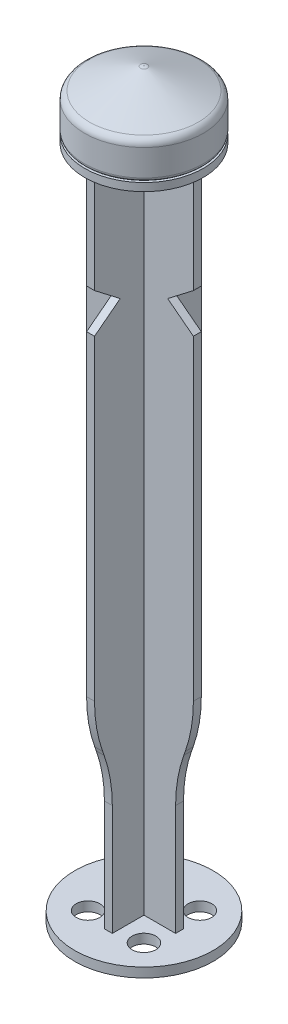
SolidWorks part; units mm, degrees
ref_plane "Front Plane" through (0, 0, 0) normal (0, 0, 1) x (1, 0, 0)
ref_plane "Top Plane" through (0, 0, 0) normal (0, 1, 0) x (1, 0, 0)
ref_plane "Right Plane" through (0, 0, 0) normal (1, 0, 0) x (0, 0, -1)
sketch "Sketch1" plane through (0, 0, 0) normal (0, 1, 0) x (1, 0, 0)
  circle A0 centre (0, 0) radius 8.75
  dimension "D1" = 17.5
extrude "Boss-Extrude1" add sketch "Sketch1" along normal blind 1.2
sketch "Sketch2" plane through (0, 1.2, 0) normal (0, 1, 0) x (1, 0, 0)
  line L1 (-0.5, 4.5) -> (0.5, 4.5)
  line L2 (-0.5, 4.5) -> (-0.5, 0)
  line L3 (-0.5, 0) -> (0.5, 0)
  line L4 (0.5, 4.5) -> (0.5, 0)
  point P9 (0, 0)
  dimension "D1" = 4.5
  dimension "D2" = 1
sketch "Sketch3" plane through (0, 0, 0) normal (1, 0, 0) x (0, 0, -1)
  line L0 (0, 1.2) -> (0, 85.2)
  line L1 (5.5318, 21.2068) -> (5.7182, 21.7331)
  line L4 (8.75, 1.2) -> (-8.75, 1.2) construction
  line L5 (4.5, 1.2) -> (4.5, 15.2)
  line L7 (6.75, 27.7399) -> (6.75, 67.7)
  line L8 (6.75, 67.7) -> (3.5, 70.2)
  line L9 (3.5, 70.2) -> (6.75, 72.7)
  line L10 (6.75, 72.7) -> (6.75, 85.2)
  line L11 (6.75, 85.2) -> (0, 85.2)
  line L12 (4.5, 1.2) -> (0, 1.2)
  arc A2 (6.75, 27.7399) -> (5.7182, 21.7331) centre (-11.25, 27.7399) cw
  arc A3 (4.5, 15.2) -> (5.5318, 21.2068) centre (22.5, 15.2) cw
  dimension "D9" = 14
  dimension "D8" = 18
  dimension "D1" = 84
  dimension "D2" = 4.5
  dimension "D3" = 6.75
  dimension "D4" = 6.75
  dimension "D5" = 3.5
  dimension "D6" = 15
  dimension "D7" = 5
  dimension "D10" = 26.5399
extrude "Boss-Extrude2" add sketch "Sketch3" against normal up to vertex (0.5 mm away) and the other way up to vertex (0.5 mm away) up to point (-0.5, 1.2, 0) other way up to point (0.5, 1.2, 0)
pattern_circular "CirPattern1" count 4 over 360 about axis through (0, 0, 0) along (0, 1, 0) of "Boss-Extrude2"
sketch "Sketch4" plane through (0, 85.2, 0) normal (0, 1, 0) x (1, 0, 0)
  circle A0 centre (0, 0) radius 7.5
  dimension "D1" = 15
extrude "Boss-Extrude3" add sketch "Sketch4" along normal blind 1
sketch "Sketch5" plane through (0, 0, 0) normal (1, 0, 0) x (0, 0, -1)
  line L0 (0, 86.2) -> (7, 86.2)
  line L1 (7.5, 86.7) -> (7.5, 90.0316)
  line L7 (6.8824, 90.9556) -> (0.4336, 93.624)
  line L8 (0, 93.7) -> (0, 86.2)
  line L12 (7.5, 86.2) -> (-7.5, 86.2) construction
  line L13 (0.0513, 93.7) -> (0, 93.7)
  arc A0 (7.5, 90.0316) -> (6.8824, 90.9556) centre (6.5, 90.0316) ccw
  arc A1 (7, 86.2) -> (7.5, 86.7) centre (7, 86.7) ccw
  arc A2 (0.4336, 93.624) -> (0.0513, 93.7) centre (0.0513, 92.7) ccw
  point P7 (7.5, 90.7)
  point P27 (7.5, 86.2)
  point P32 (0.25, 93.7)
  dimension "D4" = 1
  dimension "D5" = 0.5
  dimension "D7" = 1
  dimension "D1" = 4.5
  dimension "D2" = 7.5
  dimension "D3" = 7.5
  dimension "D6" = 0.25
revolve "Revolve1" add sketch "Sketch5" angle 360 about L8
sketch "Sketch6" plane through (0, 0, 0) normal (0, -1, 0) x (1, 0, 0)
  line L0 (0, 0) -> (0, -4.5) construction
  line L1 (-0.5, -4.5) -> (0.5, -4.5) construction
  line L2 (0, 0) -> (3.5355, -3.5355) construction
  circle A0 centre (3.5355, -3.5355) radius 1.5
  point P7 (2.7175, -2.0126)
  dimension "D1" = 3
  dimension "D2" = 5
  dimension "D3" = 45
extrude "Cut-Extrude1" cut sketch "Sketch6" against normal up to next
pattern_circular "CirPattern2" count 4 over 360 about axis through (0, 0, 0) along (0, 1, 0) of "Cut-Extrude1"
